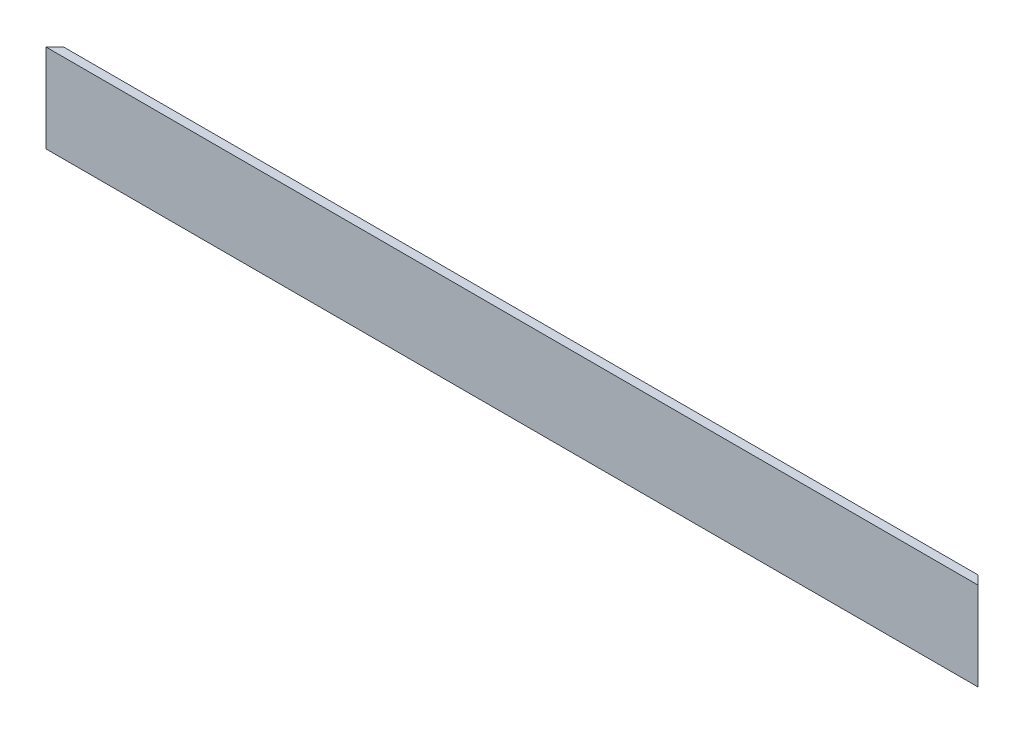
SolidWorks part; units mm, degrees
ref_plane "Alzado" through (0, 0, 0) normal (0, 0, 1) x (1, 0, 0)
ref_plane "Planta" through (0, 0, 0) normal (0, 1, 0) x (1, 0, 0)
ref_plane "Vista lateral" through (0, 0, 0) normal (1, 0, 0) x (0, 0, -1)
sketch "Croquis1" plane through (0, 0, 0) normal (0, 1, 0) x (1, 0, 0)
  line L1 (-528, 5) -> (528, 5)
  line L2 (-528, 5) -> (-528, -5)
  line L3 (-528, -5) -> (528, -5)
  line L4 (528, 5) -> (528, -5)
  line L5 (-528, 5) -> (528, -5) construction
  line L6 (-528, -5) -> (528, 5) construction
  point P0 (0, 0)
  dimension "D1" = 1056
  dimension "D2" = 10
extrude "Saliente-Extruir1" add sketch "Croquis1" along normal blind 100
sketch "Croquis2" plane through (0, 100, 0) normal (0, 1, 0) x (1, 0, 0)
  line L0 (-528, -5) -> (-518, 5)
  line L1 (528, 5) -> (-528, 5) construction
  line L2 (-518, 5) -> (-528, 5)
  line L3 (-528, 5) -> (-528, -5)
  line L4 (-528, -5) -> (528, -5) construction
  line L5 (0, 5) -> (0, -5) construction
  line L6 (518, 5) -> (528, 5)
  line L7 (528, -5) -> (518, 5)
  line L8 (528, 5) -> (528, -5)
  dimension "D1" = 45
extrude "Cortar-Extruir1" cut sketch "Croquis2" against normal blind 100
sketch "Croquis3" plane through (0, 0, -5) normal (0, 0, -1) x (-1, 0, 0)
  line L0 (-528, 100) -> (-528, 0) construction
  line L1 (-528, 98.75) -> (528, 98.75)
  line L2 (-528, 98.75) -> (-528, 1.25)
  line L3 (-528, 1.25) -> (528, 1.25)
  line L4 (528, 98.75) -> (528, 1.25)
  line L5 (528, 100) -> (528, 0) construction
  line L6 (-518, 100) -> (518, 100) construction
  line L7 (-518, 0) -> (518, 0) construction
  dimension "D1" = 1.25
  dimension "D2" = 1.25
extrude "Cortar-Extruir2" cut sketch "Croquis3" against normal blind 8
